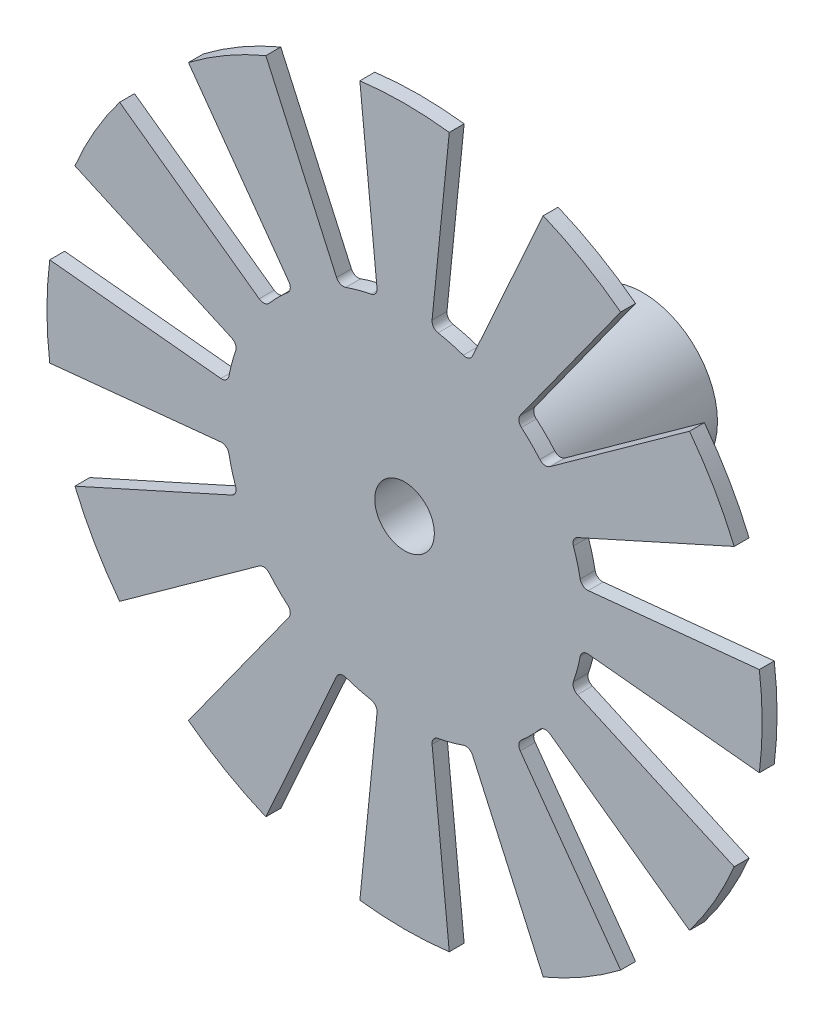
SolidWorks part; units mm, degrees
ref_plane "Alzado" through (0, 0, 0) normal (0, 0, 1) x (1, 0, 0)
ref_plane "Planta" through (0, 0, 0) normal (0, 1, 0) x (1, 0, 0)
ref_plane "Vista lateral" through (0, 0, 0) normal (1, 0, 0) x (0, 0, -1)
sketch "Croquis1" plane through (0, 0, 0) normal (0, 0, 1) x (1, 0, 0)
  line L0 (-0.9, 5.9321) -> (-1.5, 11.9059)
  line L1 (0.9, 5.9321) -> (1.5, 11.9059)
  line L2 (2.1866, 5.5874) -> (4.6539, 11.0608)
  line L3 (3.7455, 4.6874) -> (7.252, 9.5608)
  line L4 (4.6874, 3.7455) -> (9.5608, 7.252)
  line L5 (5.5874, 2.1866) -> (11.0608, 4.6539)
  line L6 (5.9321, 0.9) -> (11.9059, 1.5)
  line L7 (5.9321, -0.9) -> (11.9059, -1.5)
  line L8 (5.5874, -2.1866) -> (11.0608, -4.6539)
  line L9 (4.6874, -3.7455) -> (9.5608, -7.252)
  line L10 (3.7455, -4.6874) -> (7.252, -9.5608)
  line L11 (2.1866, -5.5874) -> (4.6539, -11.0608)
  line L12 (0.9, -5.9321) -> (1.5, -11.9059)
  line L13 (-0.9, -5.9321) -> (-1.5, -11.9059)
  line L14 (-2.1866, -5.5874) -> (-4.6539, -11.0608)
  line L15 (-3.7455, -4.6874) -> (-7.252, -9.5608)
  line L16 (-4.6874, -3.7455) -> (-9.5608, -7.252)
  line L17 (-5.5874, -2.1866) -> (-11.0608, -4.6539)
  line L18 (-5.9321, -0.9) -> (-11.9059, -1.5)
  line L19 (-5.9321, 0.9) -> (-11.9059, 1.5)
  line L20 (-5.5874, 2.1866) -> (-11.0608, 4.6539)
  line L21 (-4.6874, 3.7455) -> (-9.5608, 7.252)
  line L22 (-3.7455, 4.6874) -> (-7.252, 9.5608)
  line L23 (-2.1866, 5.5874) -> (-4.6539, 11.0608)
  circle A0 centre (0, 0) radius 12 construction
  circle A1 centre (0, 0) radius 1
  arc A2 (-5.9321, -0.9) -> (-5.5874, -2.1866) centre (0, 0) ccw
  arc A3 (-1.5, 11.9059) -> (1.5, 11.9059) centre (0, 0) cw
  arc A5 (4.6539, 11.0608) -> (7.252, 9.5608) centre (0, 0) cw
  arc A7 (9.5608, 7.252) -> (11.0608, 4.6539) centre (0, 0) cw
  arc A9 (11.9059, 1.5) -> (11.9059, -1.5) centre (0, 0) cw
  arc A11 (11.0608, -4.6539) -> (9.5608, -7.252) centre (0, 0) cw
  arc A13 (7.252, -9.5608) -> (4.6539, -11.0608) centre (0, 0) cw
  arc A15 (1.5, -11.9059) -> (-1.5, -11.9059) centre (0, 0) cw
  arc A17 (-4.6539, -11.0608) -> (-7.252, -9.5608) centre (0, 0) cw
  arc A19 (-9.5608, -7.252) -> (-11.0608, -4.6539) centre (0, 0) cw
  arc A21 (-11.9059, -1.5) -> (-11.9059, 1.5) centre (0, 0) cw
  arc A23 (-11.0608, 4.6539) -> (-9.5608, 7.252) centre (0, 0) cw
  arc A25 (-7.252, 9.5608) -> (-4.6539, 11.0608) centre (0, 0) cw
  arc A27 (-5.5874, 2.1866) -> (-5.9321, 0.9) centre (0, 0) ccw
  arc A39 (-3.7455, 4.6874) -> (-4.6874, 3.7455) centre (0, 0) ccw
  arc A51 (-0.9, 5.9321) -> (-2.1866, 5.5874) centre (0, 0) ccw
  arc A63 (2.1866, 5.5874) -> (0.9, 5.9321) centre (0, 0) ccw
  arc A75 (4.6874, 3.7455) -> (3.7455, 4.6874) centre (0, 0) ccw
  arc A87 (5.9321, 0.9) -> (5.5874, 2.1866) centre (0, 0) ccw
  arc A99 (5.5874, -2.1866) -> (5.9321, -0.9) centre (0, 0) ccw
  arc A111 (3.7455, -4.6874) -> (4.6874, -3.7455) centre (0, 0) ccw
  arc A123 (0.9, -5.9321) -> (2.1866, -5.5874) centre (0, 0) ccw
  arc A135 (-2.1866, -5.5874) -> (-0.9, -5.9321) centre (0, 0) ccw
  arc A147 (-4.6874, -3.7455) -> (-3.7455, -4.6874) centre (0, 0) ccw
  arc A159 (-5.9321, -0.9) -> (-5.5874, -2.1866) centre (0, 0) ccw [skipped]
  arc A160 (-5.9321, -0.9) -> (-5.5874, -2.1866) centre (0, 0) ccw [skipped]
  arc A161 (-5.9321, -0.9) -> (-5.5874, -2.1866) centre (0, 0) ccw [skipped]
  arc A162 (-5.9321, -0.9) -> (-5.5874, -2.1866) centre (0, 0) ccw [skipped]
  arc A163 (-5.9321, -0.9) -> (-5.5874, -2.1866) centre (0, 0) ccw [skipped]
  arc A164 (-5.9321, -0.9) -> (-5.5874, -2.1866) centre (0, 0) ccw [skipped]
  arc A165 (-5.9321, -0.9) -> (-5.5874, -2.1866) centre (0, 0) ccw [skipped]
  arc A166 (-5.9321, -0.9) -> (-5.5874, -2.1866) centre (0, 0) ccw [skipped]
  arc A167 (-5.9321, -0.9) -> (-5.5874, -2.1866) centre (0, 0) ccw [skipped]
  arc A168 (-5.9321, -0.9) -> (-5.5874, -2.1866) centre (0, 0) ccw [skipped]
  arc A169 (-5.9321, -0.9) -> (-5.5874, -2.1866) centre (0, 0) ccw [skipped]
  point P67 (0, 0)
  dimension "D1" = 24
  dimension "D2" = 2
  dimension "D3" = 12
  dimension "D4" = 3
  dimension "D5" = 1.8
  dimension "D6" = 0.9
  dimension "D7" = 1.5
  dimension "D8" = 12
extrude "Saliente-Extruir2" add sketch "Croquis1" along normal blind 0.5
fillet "Redondeo1" radius 0.25 24 edges at (-4.6874, 3.7455, 0.25) (-5.9321, -0.9, 0.25) (-5.5874, -2.1866, 0.25) (-4.6874, -3.7455, 0.25) (-3.7455, -4.6874, 0.25) (-2.1866, -5.5874, 0.25) (-0.9, -5.9321, 0.25) (0.9, -5.9321, 0.25) (2.1866, -5.5874, 0.25) (3.7455, -4.6874, 0.25) (4.6874, -3.7455, 0.25) (5.5874, -2.1866, 0.25) (5.9321, -0.9, 0.25) (5.9321, 0.9, 0.25) (5.5874, 2.1866, 0.25) (4.6874, 3.7455, 0.25) (3.7455, 4.6874, 0.25) (2.1866, 5.5874, 0.25) (0.9, 5.9321, 0.25) (-0.9, 5.9321, 0.25) (-2.1866, 5.5874, 0.25) (-5.9321, 0.9, 0.25) (-5.5874, 2.1866, 0.25) (-3.7455, 4.6874, 0.25)
sketch "Croquis2" plane through (0, 0, 0) normal (0, 0, -1) x (-1, 0, 0)
  circle A0 centre (0, 0) radius 1
  circle A1 centre (0, 0) radius 2.5
  dimension "D1" = 5
extrude "Saliente-Extruir3" add sketch "Croquis2" along normal blind 7.5
equation "\"D6@Croquis1\"=\"D5@Croquis1\"/2"
equation "\"D7@Croquis1\"=\"D4@Croquis1\"/2"
